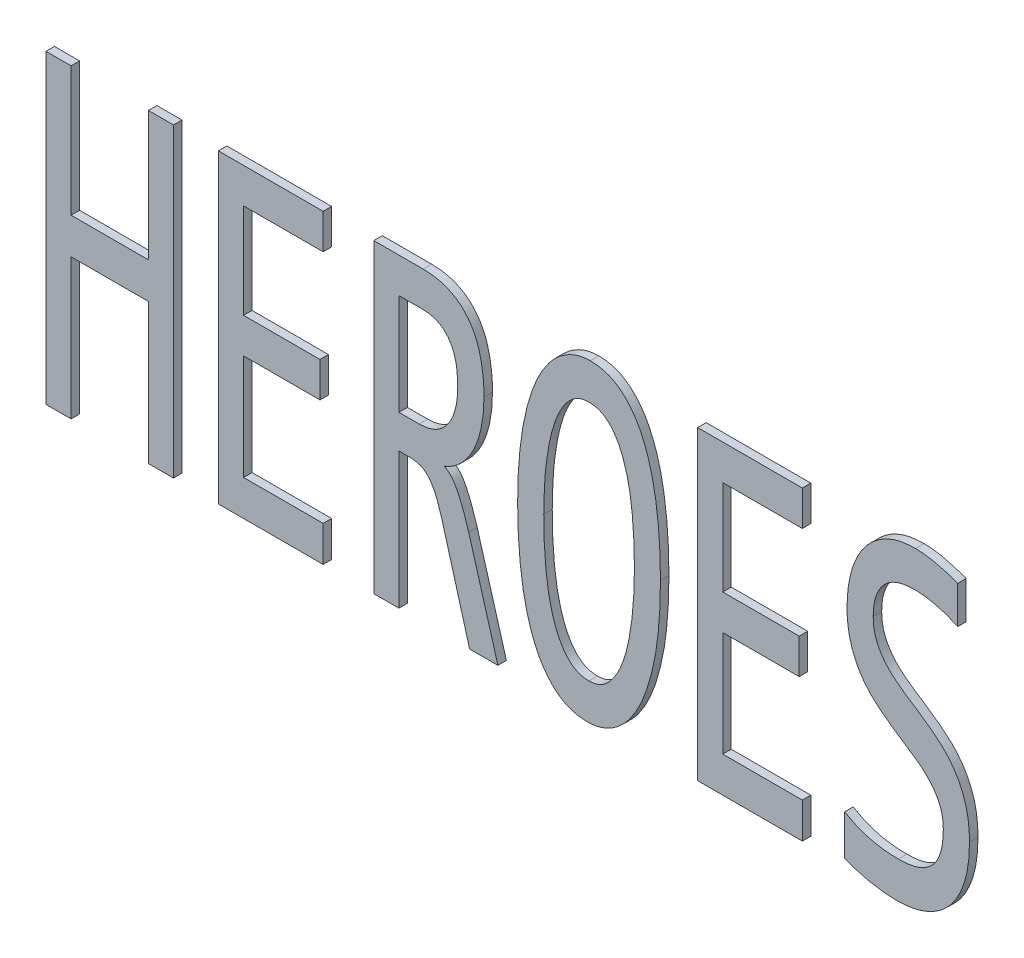
SolidWorks part; units mm, degrees
ref_plane "Front Plane" through (0, 0, 0) normal (0, 0, 1) x (1, 0, 0)
ref_plane "Top Plane" through (0, 0, 0) normal (0, 1, 0) x (1, 0, 0)
ref_plane "Right Plane" through (0, 0, 0) normal (1, 0, 0) x (0, 0, -1)
sketch "Sketch1" plane through (0, 0, 0) normal (0, 0, 1) x (1, 0, 0)
  text T0 "HEROES" font "Consolas" height 914.4
extrude "Boss-Extrude1" add sketch "Sketch1" along normal blind 25.4
